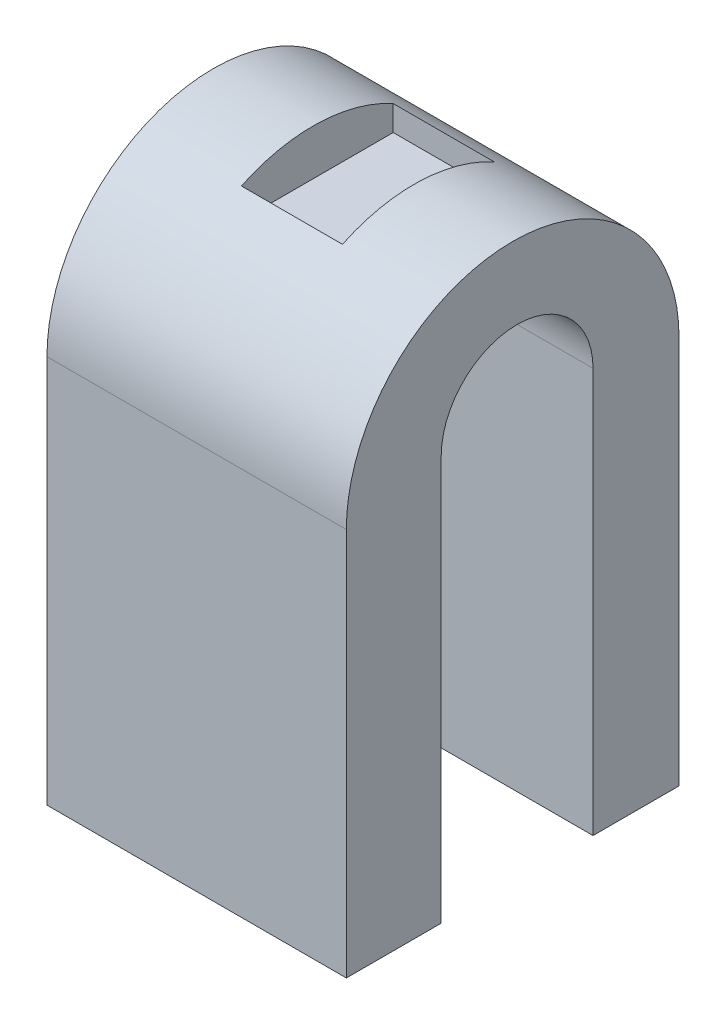
SolidWorks part; units mm, degrees
ref_plane "Front Plane" through (0, 0, 0) normal (0, 0, 1) x (1, 0, 0)
ref_plane "Top Plane" through (0, 0, 0) normal (0, 1, 0) x (1, 0, 0)
ref_plane "Right Plane" through (0, 0, 0) normal (1, 0, 0) x (0, 0, -1)
sketch "Sketch7" plane through (0, 0, 0) normal (1, 0, 0) x (0, 0, -1)
  line L1 (0, 0) -> (55.5618, 0)
  line L2 (0, 0) -> (0, 64.8619)
  line L3 (0, 64.8619) -> (55.5618, 64.8619)
  line L4 (55.5618, 0) -> (55.5618, 64.8619)
  circle A0 centre (27.7809, 64.8619) radius 27.7809
extrude "Boss-Extrude3" add sketch "Sketch7" along normal blind 50 contours L3 A0 | L3 A0 | A0 L2 L1 L4
sketch "Sketch8" plane through (50, 0, 0) normal (1, 0, 0) x (0, 0, -1)
  line L1 (15.8431, 67.5822) -> (41.1968, 67.5822)
  line L2 (15.8431, 67.5822) -> (15.8431, -0.7479)
  line L3 (15.8431, -0.7479) -> (41.1968, -0.7479)
  line L4 (41.1968, 67.5822) -> (41.1968, -0.7479)
  circle A0 centre (28.5199, 67.5822) radius 12.6769
  line M3 (0, 0) -> (55.5618, 0)
extrude "Cut-Extrude2" cut sketch "Sketch8" against normal through all contours L1 A0 | L1 A0 | A0 L2 L4 M3
sketch "Sketch9" plane through (0, 0, -41.1968) normal (0, 0, 1) x (1, 0, 0)
  line L0 (0, 67.5822) -> (-21.7688, 67.5822) construction
  line L1 (-21.7688, 67.5822) -> (66.9217, 67.5822) construction
sketch "Sketch10" plane through (0, 0, -15.8431) normal (0, 0, -1) x (-1, 0, 0)
  line L0 (0, 67.5822) -> (20.5972, 67.5822) construction
  line L1 (20.5972, 67.5822) -> (-68.6103, 67.5822) construction
ref_plane "Plane1" through (0, 85, 0) normal (0, 1, 0) x (1, 0, 0)
sketch "Sketch12" plane through (0, 85, 0) normal (0, 1, 0) x (1, 0, 0)
  line L0 (-21.7688, 41.1968) -> (66.9217, 41.1968) construction
  line L1 (16.6327, 41.1968) -> (33.5085, 41.1968)
  line L2 (16.6327, 41.1968) -> (16.6327, 15.8431)
  line L3 (16.6327, 15.8431) -> (33.5085, 15.8431)
  line L4 (33.5085, 41.1968) -> (33.5085, 15.8431)
  line L5 (-20.5972, 15.8431) -> (68.6103, 15.8431) construction
extrude "Cut-Extrude3" cut sketch "Sketch12" along normal through all
